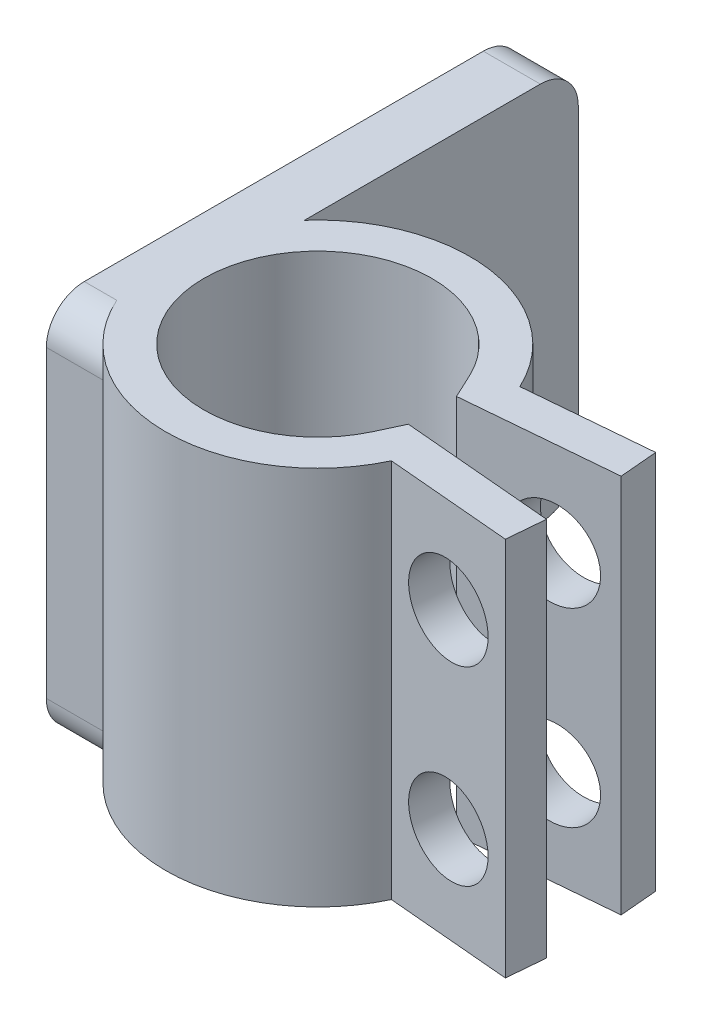
SolidWorks part; units mm, degrees
ref_plane "Front Plane" through (0, 0, 0) normal (0, 0, 1) x (1, 0, 0)
ref_plane "Top Plane" through (0, 0, 0) normal (0, 1, 0) x (1, 0, 0)
ref_plane "Right Plane" through (0, 0, 0) normal (1, 0, 0) x (0, 0, -1)
sketch "Sketch1" plane through (0, 0, 0) normal (0, 1, 0) x (1, 0, 0)
  line L0 (0, 0) -> (0, 31.75)
  line L1 (0, 31.75) -> (3.81, 31.75)
  line L2 (3.81, 31.75) -> (3.81, 0) construction
  line L3 (3.81, 0) -> (0, 0)
  line L5 (3.81, 6.7202) -> (19.05, 6.7202) construction
  line L6 (11.43, 6.7202) -> (18.3361, 3.4999) construction
  line L7 (11.43, 6.7202) -> (18.3361, 9.9406) construction
  line L8 (18.3361, 3.4999) -> (20.6381, 2.4264) construction
  line L9 (18.3361, 9.9406) -> (20.6381, 11.014) construction
  line L10 (3.81, 13.4404) -> (3.81, 31.75)
  line L11 (0, 15.875) -> (3.81, 15.875) construction
  line L12 (18.3361, 9.9406) -> (19.0877, 8.3287)
  line L13 (19.0877, 8.3287) -> (29.209, 9.2142)
  line L14 (29.209, 9.2142) -> (28.9877, 11.7445)
  line L15 (28.9877, 11.7445) -> (20.6381, 11.014)
  line L16 (18.3361, 3.4999) -> (19.0877, 5.1118)
  line L17 (19.0877, 5.1118) -> (29.209, 4.2262)
  line L18 (29.209, 4.2262) -> (28.9877, 1.6959)
  line L19 (28.9877, 1.6959) -> (20.6381, 2.4264)
  circle A1 centre (11.43, 6.7202) radius 7.62 construction
  circle A5 centre (11.43, 6.7202) radius 10.16 construction
  arc A6 (3.81, 13.4404) -> (20.6381, 11.014) centre (11.43, 6.7202) cw
  arc A7 (3.81, 6.7202) -> (18.3361, 9.9406) centre (11.43, 6.7202) cw
  arc A8 (18.3361, 3.4999) -> (3.81, 6.7202) centre (11.43, 6.7202) cw
  arc A9 (20.6381, 2.4264) -> (3.81, 0) centre (11.43, 6.7202) cw
  dimension "D1" = 15.24
  dimension "D2" = 2.54
  dimension "D4" = 25
  dimension "D6" = 31.75
  dimension "D7" = 2.54
  dimension "D3" = 25
  dimension "D5" = 3.81
  dimension "D8" = 2.54
  dimension "D9" = 110
  dimension "D10" = 110
  dimension "D11" = 10.16
extrude "Boss-Extrude1" add sketch "Sketch1" along normal blind 25.4
sketch "Sketch2" plane through (0, 0, 0) normal (-1, 0, 0) x (0, 0, 1)
  line L0 (-31.75, 12.7) -> (-21.59, 12.7) construction
  line L1 (-31.75, 25.4) -> (-31.75, 0) construction
  circle A0 centre (-21.59, 12.7) radius 3.175
  dimension "D1" = 6.35
  dimension "D2" = 10.16
extrude "Cut-Extrude1" cut sketch "Sketch2" against normal up to next
fillet "Fillet1" radius 2.54 4 edges at (1.905, 25.4, -31.75) (1.905, 25.4, 0) (1.905, 0, 0) (1.905, 0, -31.75)
sketch "Sketch3" plane through (-0.7995, 0, -9.1385) normal (-0.0872, 0, -0.9962) x (-0.9962, 0, 0.0872)
  line L0 (-25.7102, 25.4) -> (-25.7102, 0) construction
  line L1 (-29.901, 25.4) -> (-21.5195, 25.4) construction
  line L2 (-29.901, 0) -> (-21.5195, 0) construction
  circle A0 centre (-25.7102, 19.05) radius 2.921
  circle A1 centre (-25.7102, 6.35) radius 2.921
  dimension "D1" = 5.842
  dimension "D2" = 5.842
  dimension "D3" = 6.35
  dimension "D4" = 6.35
extrude "Cut-Extrude2" cut sketch "Sketch3" against normal up to next
sketch "Sketch4" plane through (0.3674, 0, -4.1999) normal (-0.0872, 0, 0.9962) x (0.9962, 0, 0.0872)
  line L0 (24.5388, 25.4) -> (24.5388, 0) construction
  line L1 (20.3481, 25.4) -> (28.7296, 25.4) construction
  line L2 (20.3481, 0) -> (28.7296, 0) construction
  circle A0 centre (24.5388, 19.05) radius 2.921
  circle A1 centre (24.5388, 6.35) radius 2.921
  dimension "D1" = 5.842
  dimension "D3" = 5.842
  dimension "D2" = 6.35
  dimension "D4" = 6.35
extrude "Cut-Extrude3" cut sketch "Sketch4" against normal up to next
